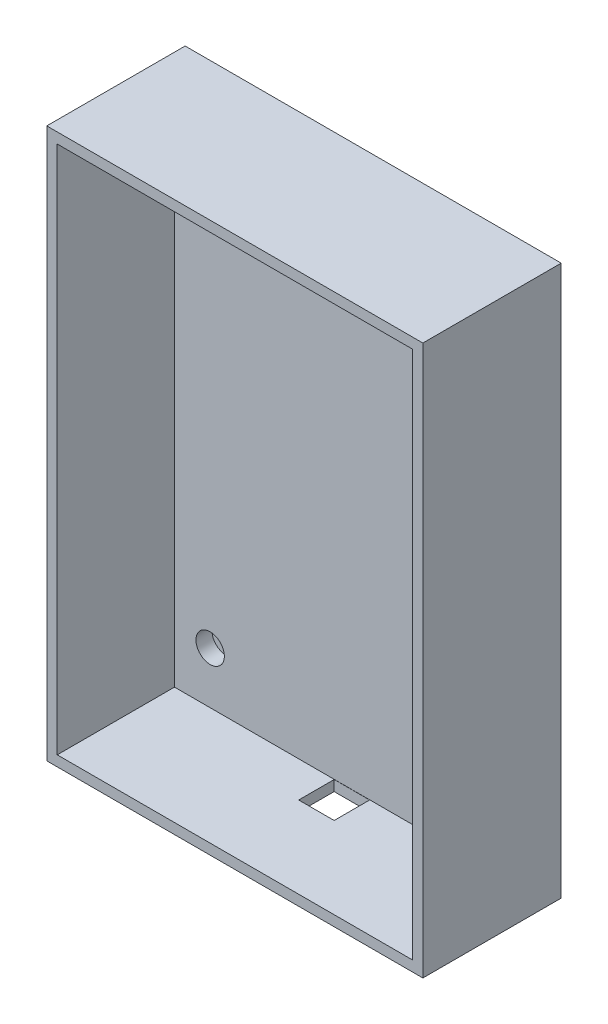
SolidWorks part; units mm, degrees
ref_plane "정면" through (0, 0, 0) normal (0, 0, 1) x (1, 0, 0)
ref_plane "윗면" through (0, 0, 0) normal (0, 1, 0) x (1, 0, 0)
ref_plane "우측면" through (0, 0, 0) normal (1, 0, 0) x (0, 0, -1)
sketch "스케치1" plane through (0, 0, 0) normal (0, 0, 1) x (1, 0, 0)
  line L1 (-53, 77.5) -> (53, 77.5)
  line L2 (-53, 77.5) -> (-53, -77.5)
  line L3 (-53, -77.5) -> (53, -77.5)
  line L4 (53, 77.5) -> (53, -77.5)
  line L5 (-53, 77.5) -> (53, -77.5) construction
  line L6 (-53, -77.5) -> (53, 77.5) construction
  point P0 (0, 0)
  dimension "D1" = 106
  dimension "D2" = 155
extrude "보스-돌출1" add sketch "스케치1" along normal blind 36
shell "쉘1" thickness 2.95
sketch "스케치2" plane through (0, -77.5, 0) normal (0, -1, 0) x (1, 0, 0)
  line L0 (-53, 0) -> (53, 0) construction
  line L5 (-5, 13) -> (5, 13)
  line L6 (-5, 13) -> (-5, 3)
  line L7 (-5, 3) -> (5, 3)
  line L8 (5, 13) -> (5, 3)
  line L9 (-5, 13) -> (5, 3) construction
  line L10 (-5, 3) -> (5, 13) construction
  point P0 (0, 8)
  point P8 (0, 0)
  point P9 (0, 8.8358)
  point P10 (0, 0)
  dimension "D1" = 3
  dimension "D2" = 10
  dimension "D3" = 10
extrude "컷-돌출1" cut sketch "스케치2" against normal blind 36
sketch "스케치3" plane through (0, 0, 0) normal (0, 0, -1) x (-1, 0, 0)
  line L1 (-53, 77.5) -> (53, 77.5)
  line L2 (-53, 77.5) -> (-53, -77.5)
  line L3 (-53, -77.5) -> (53, -77.5)
  line L4 (53, 77.5) -> (53, -77.5)
  point P5 (53, -77.5)
extrude "보스-돌출2" add sketch "스케치3" along normal blind 3
hole_wizard "M4 소켓 머리 캡 나사용 카운터보어1" positions "스케치4" profile "스케치6" counterbore size "M4" standard "KS"
sketch "스케치4" plane through (0, 0, 2.95) normal (0, 0, 1) x (1, 0, 0)
  point P0 (-40, 60)
  point P2 (40, 60)
  point P4 (40, -60)
  point P6 (-40, -60)
  point P13 (0, 0)
  point P15 (0, 0)
  point P16 (0, 0)
  point P17 (0, 0)
  point P18 (0, 0)
  point P19 (0, 0)
  point P20 (0, 0)
  point P21 (30, 44.6638)
  point P22 (0, 0)
  dimension "D1" = 40
  dimension "D2" = 80
  dimension "D3" = 120
  dimension "D4" = 60
sketch "스케치6" plane through (-40, 60, 2.95) normal (1, 0, 0) x (0, -1, 0)
  line L0 (0, 0) -> (0, 46.3519)
  line L1 (0, 46.3519) -> (2.25, 45)
  line L2 (2.25, 45) -> (2.25, 4.5)
  line L3 (2.25, 4.5) -> (4, 4.5)
  line L4 (4, 4.5) -> (4, 0)
  line L5 (4, 0) -> (0, 0)
  line L10 (0, 46.3519) -> (-2.25, 45) construction
  line L11 (0, -6.35) -> (0, 107.95) construction
  dimension "구멍 지름" = 4.5
  dimension "구멍 깊이" = 45
  dimension "카운터보어 지름" = 8
  dimension "카운터보어 깊이" = 4.5
  dimension "드릴 각도" = 118
